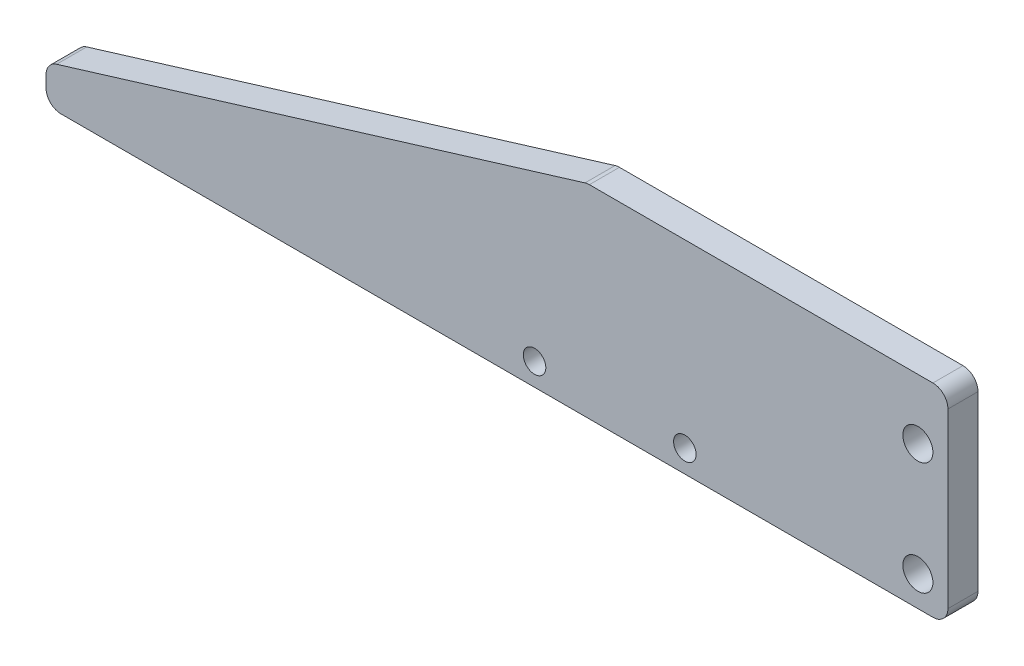
SolidWorks part; units mm, degrees
ref_plane "前视基准面" through (0, 0, 0) normal (0, 0, 1) x (1, 0, 0)
ref_plane "上视基准面" through (0, 0, 0) normal (0, 1, 0) x (1, 0, 0)
ref_plane "右视基准面" through (0, 0, 0) normal (1, 0, 0) x (0, 0, -1)
other "Configuration Table"
sketch "草图1" plane through (0, 0, 0) normal (0, 0, 1) x (1, 0, 0)
  line L1 (-60, 13.5) -> (60, 13.5)
  line L2 (-60, 13.5) -> (-60, -13.5)
  line L3 (-60, -13.5) -> (60, -13.5)
  line L4 (60, 13.5) -> (60, -13.5)
  line L5 (-60, 13.5) -> (60, -13.5) construction
  line L6 (-60, -13.5) -> (60, 13.5) construction
  circle A0 centre (56, 5.5) radius 2
  circle A1 centre (56, -9.5) radius 2
  circle A2 centre (25, -10.5) radius 1.5
  circle A3 centre (5, -10.5) radius 1.5
  point P0 (0, 0)
  dimension "D2" = 15
  dimension "D3" = 4
  dimension "D4" = 4
  dimension "D5" = 4
  dimension "D6" = 20
  dimension "D7" = 24
  dimension "D8" = 3
  dimension "D9" = 3
  dimension "D1" = 4
  dimension "120" = 120
  dimension "30" = 27
  dimension "D10" = 35
extrude "凸台-拉伸1" add sketch "草图1" along normal blind 4
sketch "草图2" plane through (0, 0, 0) normal (0, 0, -1) x (-1, 0, 0)
  line L0 (60, -8.5) -> (-12, 13.5)
  line L1 (60, 13.5) -> (60, -13.5) construction
  line L2 (-60, 13.5) -> (60, 13.5) construction
  line L3 (-12, 13.5) -> (60, 13.5)
  line L4 (60, 13.5) -> (60, -8.5)
  dimension "D1" = 22
  dimension "D2" = 72
extrude "切除-拉伸1" cut sketch "草图2" against normal blind 10
fillet "圆角1" radius 2 5 edges at (12, 13.5, 2) (60, 13.5, 2) (60, -13.5, 2) (-60, -8.5, 2) (-60, -13.5, 2)
